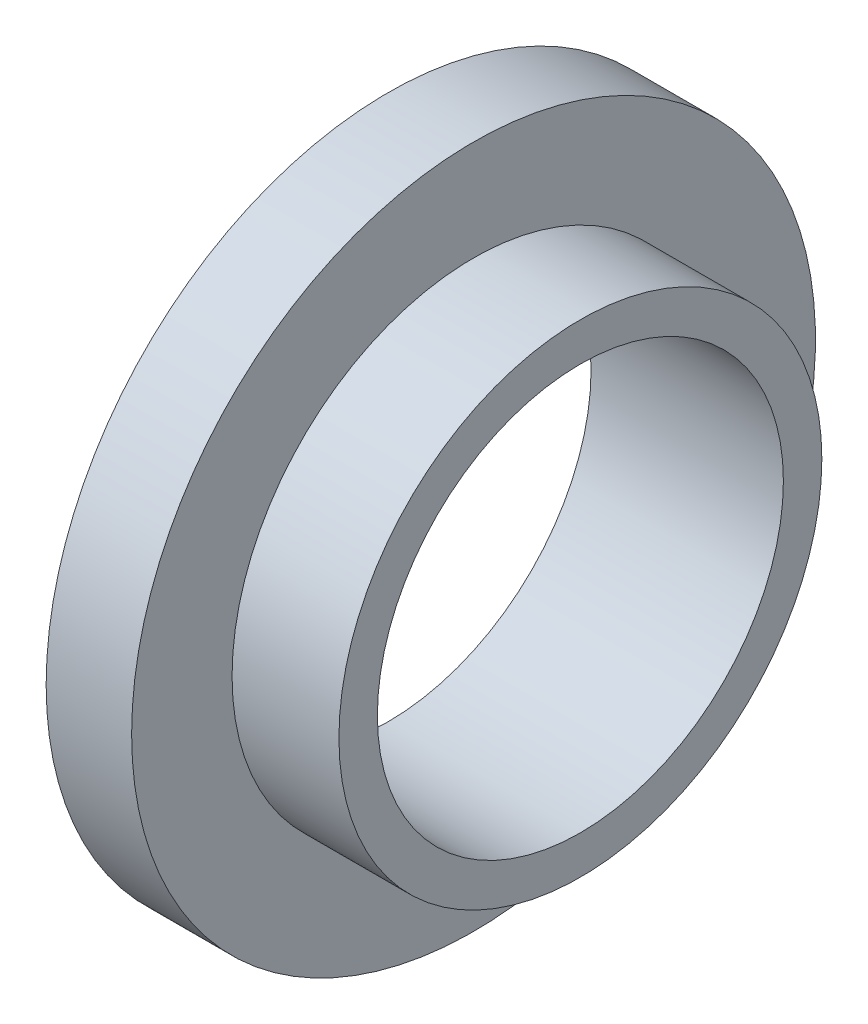
SolidWorks part; units mm, degrees
material "普通碳钢"
ref_plane "前视基准面" through (0, 0, 0) normal (0, 0, 1) x (1, 0, 0)
ref_plane "上视基准面" through (0, 0, 0) normal (0, 1, 0) x (1, 0, 0)
ref_plane "右视基准面" through (0, 0, 0) normal (1, 0, 0) x (0, 0, -1)
sketch "草图1" plane through (0, 0, 0) normal (1, 0, 0) x (0, 0, -1)
  circle A0 centre (0, 0) radius 80
  dimension "D1" = 160
extrude "凸台-拉伸1" add sketch "草图1" along normal blind 45
sketch "草图2" plane through (45, 0, 0) normal (1, 0, 0) x (0, 0, -1)
  circle A0 centre (0, 0) radius 47.5
  dimension "D1" = 95
extrude "切除-拉伸1" cut sketch "草图2" against normal through all
sketch "草图3" plane through (45, 0, 0) normal (1, 0, 0) x (0, 0, -1)
  circle A0 centre (0, 0) radius 56.5
  dimension "D1" = 113
extrude "切除-拉伸2" cut sketch "草图3" against normal offset from surface (25 mm away) 20 flip side to cut up to face at (0, 0, -47.5)
